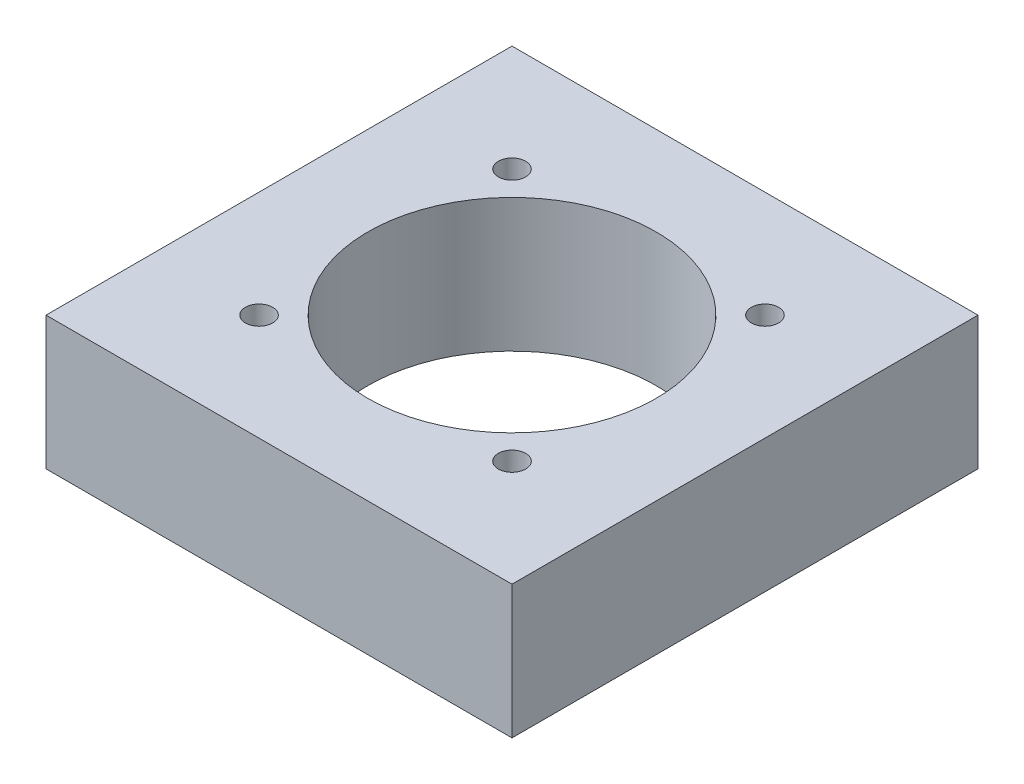
SolidWorks part; units mm, degrees
ref_plane "Front" through (0, 0, 0) normal (0, 0, 1) x (1, 0, 0)
ref_plane "Top" through (0, 0, 0) normal (0, 1, 0) x (1, 0, 0)
ref_plane "Right" through (0, 0, 0) normal (1, 0, 0) x (0, 0, -1)
sketch "Sketch2" plane through (0, 0, 0) normal (0, 1, 0) x (1, 0, 0)
  line L1 (-35, -35) -> (35, -35)
  line L2 (-35, -35) -> (-35, 35)
  line L3 (-35, 35) -> (35, 35)
  line L4 (35, -35) -> (35, 35)
  line L5 (-35, -35) -> (35, 35) construction
  line L6 (-35, 35) -> (35, -35) construction
  point P0 (0, 0)
  dimension "D1" = 70
extrude "Boss-Extrude1" add sketch "Sketch2" against normal blind 20
sketch "Sketch1" plane through (0, 0, 0) normal (0, 0, 1) x (1, 0, 0)
  line L0 (0, 0) -> (0, -14) construction
  line L1 (-15, 0) -> (15, 0) construction
  line L2 (-15, 0) -> (-15, -9) construction
  line L3 (-15, -9) -> (15, -9) construction
  line L4 (15, 0) -> (15, -9) construction
  line L5 (0, 0) -> (18, 0) construction
  line L6 (18, 0) -> (15.6756, -14.676) construction
  line L7 (-15, -20) -> (15, -20) construction
  line L8 (-15, -17) -> (15, -17) construction
  line L9 (-15, -14) -> (15, -14) construction
  line L10 (18, 0) -> (18, 4) construction
  line L11 (18, 4) -> (0, 4) construction
  line L12 (0, 4) -> (0, 0) construction
  line L13 (0, -17.2) -> (0, 0)
  line L14 (0, 0) -> (21.2417, 0)
  line L15 (-35, 0) -> (35, 0) construction
  line L16 (21.2417, 0) -> (21.1589, -0.5115)
  spline S0 degree 3 poles (0, -14) (16.3895, -14) (17.0195, -6.0548) (18, 0) knots 0 0 0 0 1 1 1 1 construction
  spline S1 degree 1 poles (0, -17.2) (21.1589, -0.5115) knots 0 0 1 1 construction
  spline S2 degree 3 poles (0, -17.2) (0.5307, -17.2) (1.6116, -17.1835) (3.6155, -17.0859) (5.9441, -16.8449) (8.4484, -16.3701) (11.4427, -15.4929) (14.5797, -13.9372) (17.3822, -11.4027) (19.199, -8.5009) (20.2357, -5.5832) (20.7065, -3.3134) (20.9819, -1.6359) (21.0969, -0.8942) (21.1589, -0.5115) knots 0 0 0 0 0.03125 0.0625 0.125 0.1875 0.25 0.375 0.5 0.625 0.75 0.875 0.9375 1 1 1 1
  dimension "D1" = 30
  dimension "D2" = 9
  dimension "D3" = 18
  dimension "D4" = 20
  dimension "D5" = 3
  dimension "D6" = 3
  dimension "D7" = 81
  dimension "D8" = 18
  dimension "D9" = 3.2
revolve "Cut-Revolve1" cut sketch "Sketch1" angle 360 about L13
sketch "Sketch3" plane through (0, 0, 0) normal (0, 1, 0) x (1, 0, 0)
  line L0 (-32.7416, 0) -> (25.0655, 0) construction
  line L1 (-19, -19) -> (19, -19) construction
  line L2 (-19, -19) -> (-19, 19) construction
  line L3 (-19, 19) -> (19, 19) construction
  line L4 (19, -19) -> (19, 19) construction
  line L5 (-19, -19) -> (19, 19) construction
  line L6 (-19, 19) -> (19, -19) construction
  circle A0 centre (-19, 19) radius 2.05
  circle A1 centre (19, -19) radius 2.05
  circle A2 centre (-19, -19) radius 2.05
  circle A3 centre (19, 19) radius 2.05
  point P0 (0, 0)
  dimension "D2" = 4.1
  dimension "D1" = 38
extrude "Cut-Extrude1" cut sketch "Sketch3" against normal through all
sketch "Sketch4" plane through (0, 0, 0) normal (0, 1, 0) x (1, 0, 0)
  line L0 (-21.6589, 12.1774) -> (-21.6589, -14.0727) construction
  line L1 (-21.1589, 13.8832) -> (-21.1589, -14.0727) construction
  circle A0 centre (0, 0) radius 21.6589
  circle A1 centre (0, 0) radius 21.1589 construction
  dimension "D1" = 0.5
extrude "Cut-Extrude2" cut sketch "Sketch4" against normal through all
